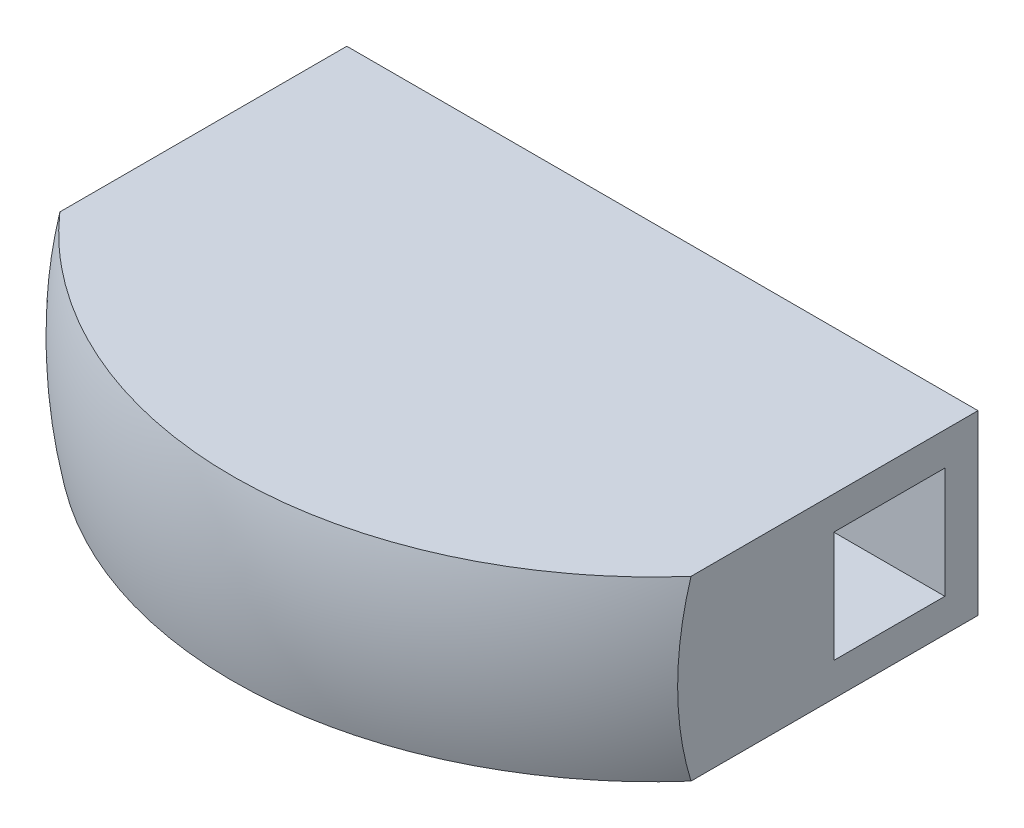
SolidWorks part; units mm, degrees
ref_plane "Front Plane" through (0, 0, 0) normal (0, 0, 1) x (1, 0, 0)
ref_plane "Top Plane" through (0, 0, 0) normal (0, 1, 0) x (1, 0, 0)
ref_plane "Right Plane" through (0, 0, 0) normal (1, 0, 0) x (0, 0, -1)
sketch "Sketch1" plane through (0, 0, 0) normal (1, 0, 0) x (0, 0, -1)
  line L1 (14.9704, -1.6764) -> (18.3232, -1.6764)
  line L2 (14.9704, -1.6764) -> (14.9704, 1.6764)
  line L3 (14.9704, 1.6764) -> (18.3232, 1.6764)
  line L4 (18.3232, -1.6764) -> (18.3232, 1.6764)
  line L5 (14.9704, -1.6764) -> (18.3232, 1.6764) construction
  line L6 (14.9704, 1.6764) -> (18.3232, -1.6764) construction
  line L7 (13.9704, -2.6764) -> (19.3232, -2.6764)
  line L8 (13.9704, -2.6764) -> (13.9704, 2.6764)
  line L9 (13.9704, 2.6764) -> (19.3232, 2.6764)
  line L10 (19.3232, -2.6764) -> (19.3232, 2.6764)
  line L11 (13.9704, -2.6764) -> (19.3232, 2.6764) construction
  line L12 (13.9704, 2.6764) -> (19.3232, -2.6764) construction
  point P0 (16.6468, 0)
  point P7 (16.6468, 0)
  dimension "D1" = 1
extrude "Boss-Extrude1" add sketch "Sketch1" along normal mid plane 19.05
sketch "Sketch2" plane through (0, -2.6764, 0) normal (0, -1, 0) x (1, 0, 0)
  line L0 (-9.525, -13.9704) -> (-9.525, -10.2581)
  line L1 (-9.525, -13.9704) -> (9.525, -13.9704)
  line L2 (9.525, -13.9704) -> (9.525, -10.2581)
  arc A0 (-9.525, -10.2581) -> (9.525, -10.2581) centre (0, -19.05) cw
  arc A1 (8.009, -8.5368) -> (-8.009, -8.5368) centre (0, -19.05) ccw construction
  dimension "D1" = 0.254
extrude "Boss-Extrude2" add sketch "Sketch2" along normal up to surface (5.3528 mm away) from surface at -5.3528 up to face at (0, -2.6764, -16.6468) starting at face at (0, 2.6764, -16.6468)
fillet "Fillet1" [suppressed] radius 1.5875
sketch "Sketch3" plane through (0, 0, 0) normal (0, 1, 0) x (1, 0, 0)
  line L0 (-9.525, 10.2581) -> (-9.525, -8.7919)
  line L1 (-9.525, -8.7919) -> (9.525, -8.7919)
  line L2 (9.525, -8.7919) -> (9.525, 10.2581)
  line L3 (-9.525, 19.3232) -> (-9.525, 10.2581)
  line L4 (9.525, 10.2581) -> (9.525, 19.3232)
  line L5 (9.525, 19.3232) -> (-9.525, 19.3232)
  line L6 (-9.525, 19.3232) -> (-9.525, 10.2581) construction
  line L7 (9.525, 10.2581) -> (9.525, 19.3232) construction
  line L8 (9.525, 19.3232) -> (-9.525, 19.3232) construction
  arc A1 (-9.525, 10.2581) -> (9.525, 10.2581) centre (0, 19.05) ccw
  arc A2 (-9.525, 10.2581) -> (9.525, 10.2581) centre (0, 19.05) ccw
  dimension "D1" = 0
revolve "Cut-Revolve1" cut sketch "Sketch3" angle 360 about L8
